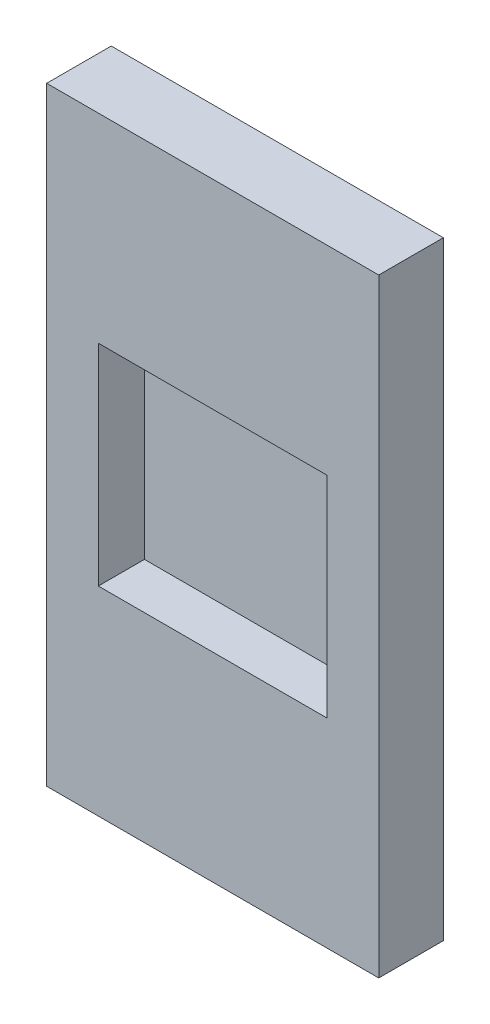
SolidWorks part; units mm, degrees
ref_plane "정면" through (0, 0, 0) normal (0, 0, 1) x (1, 0, 0)
ref_plane "윗면" through (0, 0, 0) normal (0, 1, 0) x (1, 0, 0)
ref_plane "우측면" through (0, 0, 0) normal (1, 0, 0) x (0, 0, -1)
sketch "스케치1" plane through (0, 0, 0) normal (0, 0, 1) x (1, 0, 0)
  line L1 (-9, -16.5) -> (9, -16.5)
  line L2 (-9, -16.5) -> (-9, 16.5)
  line L3 (-9, 16.5) -> (9, 16.5)
  line L4 (9, -16.5) -> (9, 16.5)
  line L5 (-9, -16.5) -> (9, 16.5) construction
  line L6 (-9, 16.5) -> (9, -16.5) construction
  point P0 (0, 0)
  dimension "D1" = 18
  dimension "D2" = 33
extrude "보스-돌출1" add sketch "스케치1" along normal blind 3.5
sketch "스케치2" plane through (0, 0, 3.5) normal (0, 0, 1) x (1, 0, 0)
  line L1 (-6.2, -5.7) -> (6.2, -5.7)
  line L2 (-6.2, -5.7) -> (-6.2, 5.7)
  line L3 (-6.2, 5.7) -> (6.2, 5.7)
  line L4 (6.2, -5.7) -> (6.2, 5.7)
  line L5 (-6.2, -5.7) -> (6.2, 5.7) construction
  line L6 (-6.2, 5.7) -> (6.2, -5.7) construction
  point P1 (0, 0)
  dimension "D1" = 12.4
  dimension "D2" = 11.4
extrude "컷-돌출1" cut sketch "스케치2" against normal blind 2.5
